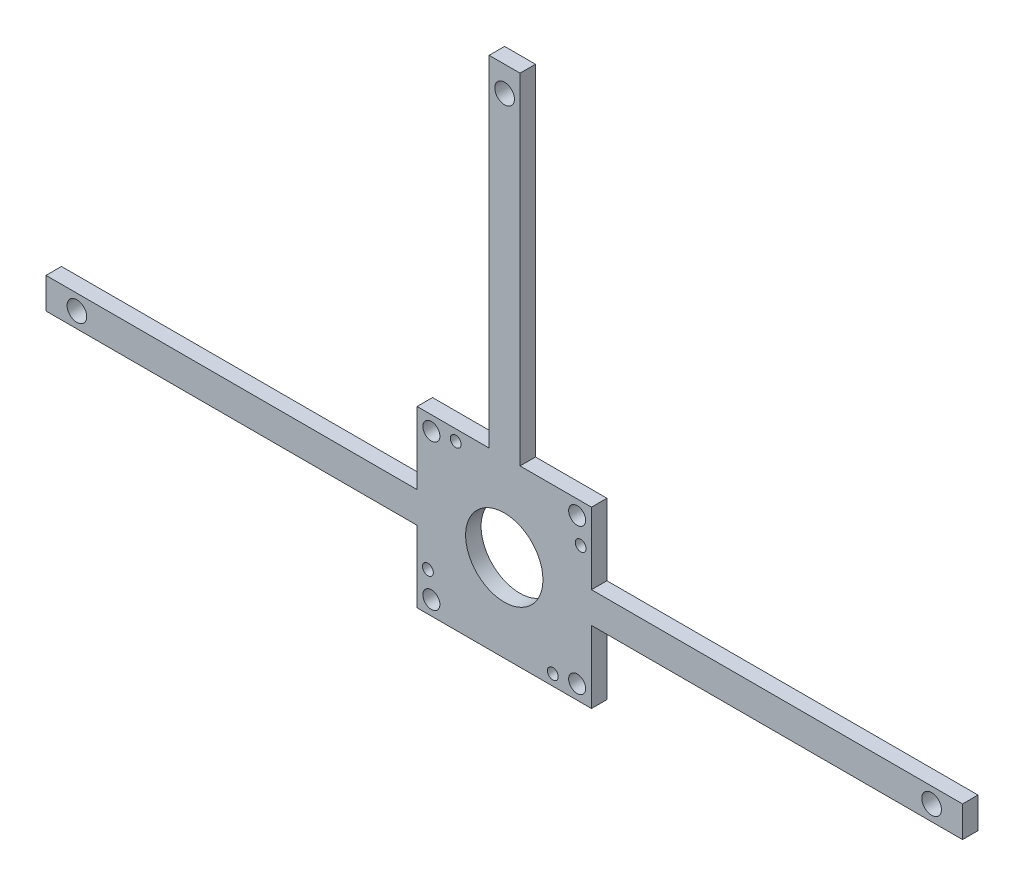
SolidWorks part; units mm, degrees
ref_plane "Alzado" through (0, 0, 0) normal (0, 0, 1) x (1, 0, 0)
ref_plane "Planta" through (0, 0, 0) normal (0, 1, 0) x (1, 0, 0)
ref_plane "Vista lateral" through (0, 0, 0) normal (1, 0, 0) x (0, 0, -1)
sketch "Croquis1" plane through (0, 0, 0) normal (0, 0, 1) x (1, 0, 0)
  line L0 (-28.2, -55.0835) -> (-28.2, -31.8)
  line L1 (-28.2, -88.2) -> (28.2, -88.2)
  line L2 (-28.2, -88.2) -> (-28.2, -65.0835)
  line L3 (-28.2, -31.8) -> (-4.8984, -31.8)
  line L4 (28.2, -88.2) -> (28.2, -64.9165)
  line L5 (-28.2, -88.2) -> (-5.4627, -65.4627) construction
  line L6 (-28.2, -31.8) -> (-5.4627, -54.5373) construction
  line L7 (-148.2, -55.0835) -> (-28.2, -55.0835)
  line L8 (-148.2, -55.0835) -> (-148.2, -65.0835)
  line L9 (-148.2, -65.0835) -> (-28.2, -65.0835)
  line L10 (148.2, -54.9165) -> (148.2, -64.9165)
  line L11 (28.2, -54.9165) -> (28.2, -31.8)
  line L12 (5.1016, 78.2) -> (-4.8984, 78.2)
  line L13 (28.2, -54.9165) -> (148.2, -54.9165)
  line L14 (5.1016, -31.8) -> (28.2, -31.8)
  line L15 (28.2, -64.9165) -> (148.2, -64.9165)
  line L16 (5.1016, -31.8) -> (5.1016, 78.2)
  line L17 (-2.3416, -67.362) -> (28.2, -88.2) construction
  line L18 (-2.3416, -52.638) -> (28.2, -31.8) construction
  line L19 (-4.8984, -31.8) -> (-4.8984, 78.2)
  circle A0 centre (-23.57, -36.43) radius 2.75
  circle A1 centre (23.57, -36.43) radius 2.75
  circle A2 centre (23.57, -83.57) radius 2.75
  circle A3 centre (-23.57, -83.57) radius 2.75
  circle A4 centre (-15.7, -35.3) radius 1.75
  circle A5 centre (24.7, -44.3) radius 1.7478
  circle A6 centre (15.7, -84.7) radius 1.75
  circle A7 centre (-24.7, -75.7) radius 1.75
  circle A8 centre (0, -60) radius 7.7254
  point P0 (0, -60)
  point P23 (-28.2, -60)
  point P29 (0, -31.8)
  dimension "D1" = 120
  dimension "D2" = 120
  dimension "D3" = 10
  dimension "D4" = 10
  dimension "D5" = 110
extrude "Saliente-Extruir1" add sketch "Croquis1" along normal blind 5
sketch "Croquis2" plane through (0, 0, 5) normal (0, 0, 1) x (1, 0, 0)
  line L0 (-148.2, -55.0835) -> (-148.2, -65.0835) construction
  line L1 (148.2, -64.9165) -> (148.2, -54.9165) construction
  line L2 (5.1016, 78.2) -> (-4.8984, 78.2) construction
  circle A0 centre (0.1016, 70) radius 3.175
  circle A1 centre (138.2, -59.9165) radius 3.175
  circle A2 centre (-138.2, -60.0835) radius 3.175
  circle A3 centre (0, -60) radius 7.7254 construction
  circle A4 centre (0, -60) radius 12.5
  point P9 (-148.2, -60.0835)
  point P14 (148.2, -59.9165)
  point P18 (0.1016, 78.2)
  dimension "D1" = 6.35
  dimension "D2" = 6.35
  dimension "D3" = 6.35
  dimension "D4" = 138.2
  dimension "D5" = 138.2
  dimension "D6" = 130
  dimension "D7" = 25
extrude "Cortar-Extruir1" cut sketch "Croquis2" against normal blind 5
